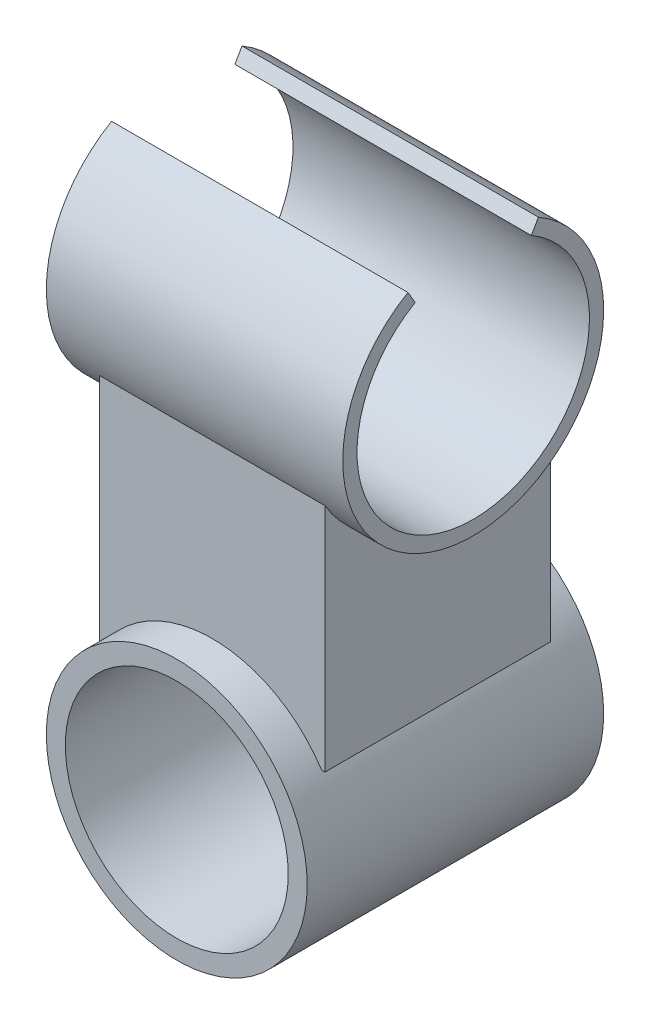
SolidWorks part; units mm, degrees
ref_plane "Front Plane" through (0, 0, 0) normal (0, 0, 1) x (1, 0, 0)
ref_plane "Top Plane" through (0, 0, 0) normal (0, 1, 0) x (1, 0, 0)
ref_plane "Right Plane" through (0, 0, 0) normal (1, 0, 0) x (0, 0, -1)
sketch "Sketch1" plane through (0, 0, 0) normal (1, 0, 0) x (0, 0, -1)
  line L0 (-5.5, 9.5263) -> (-4.9, 8.487)
  line L1 (4.9, 8.487) -> (5.5, 9.5263)
  line L2 (0, 0) -> (0, 11) construction
  line L3 (-4.9, 8.487) -> (0, 0) construction
  line L4 (0, 0) -> (4.9, 8.487) construction
  arc A0 (-4.9, 8.487) -> (4.9, 8.487) centre (0, 0) ccw
  arc A1 (-5.5, 9.5263) -> (5.5, 9.5263) centre (0, 0) ccw
  circle A3 centre (0, 0) radius 11 construction
  circle A4 centre (0, 0) radius 9.8 construction
  point P4 (9.3718, 2.8652)
  point P6 (10.5194, 3.2161)
  dimension "D1" = 22
  dimension "D2" = 1.2
  dimension "D3" = 60
  dimension "D4" = 30
extrude "Boss-Extrude1" add sketch "Sketch1" along normal mid plane 25
sketch "Sketch3" plane through (0, 0, 0) normal (0, 1, 0) x (1, 0, 0)
  line L0 (-7.9, 7.9) -> (7.9, 7.9)
  line L1 (-9.5, -9.5) -> (9.5, -9.5)
  line L2 (-9.5, -9.5) -> (-9.5, 9.5)
  line L3 (-9.5, 9.5) -> (9.5, 9.5)
  line L4 (9.5, -9.5) -> (9.5, 9.5)
  line L5 (-9.5, -9.5) -> (9.5, 9.5) construction
  line L6 (-9.5, 9.5) -> (9.5, -9.5) construction
  line L7 (7.9, -7.9) -> (7.9, 7.9)
  line L8 (-7.9, -7.9) -> (7.9, -7.9)
  line L9 (-7.9, -7.9) -> (-7.9, 7.9)
  point P0 (0, 0)
  dimension "D1" = 19
  dimension "D2" = 1.6
extrude "Boss-Extrude3" add sketch "Sketch3" against normal blind 25
sketch "Sketch2" plane through (0, 0, 0) normal (0, 0, 1) x (1, 0, 0)
  line L0 (0, -31) -> (0, 0) construction
  line L2 (-9.5, -25) -> (9.5, -25) construction
  circle A0 centre (0, -31) radius 11
  circle A1 centre (0, -31) radius 9.4
  dimension "D1" = 6
  dimension "D3" = 22
  dimension "D2" = 1.6
extrude "Boss-Extrude2" add sketch "Sketch2" along normal mid plane 25
sketch "Sketch4" plane through (0, 0, 0) normal (1, 0, 0) x (0, 0, -1)
  line L0 (-9.5, 0) -> (9.5, 0) construction
  circle A0 centre (0, 0) radius 9.8
  arc A1 (-4.9, 8.487) -> (4.9, 8.487) centre (0, 0) ccw construction
extrude "Cut-Extrude1" cut sketch "Sketch4" against normal mid plane 40
sketch "Sketch5" plane through (0, 0, 0) normal (0, 0, 1) x (1, 0, 0)
  circle A0 centre (0, -31) radius 9.4
  circle A1 centre (0, -31) radius 9.4 construction
extrude "Cut-Extrude2" cut sketch "Sketch5" against normal mid plane 40
